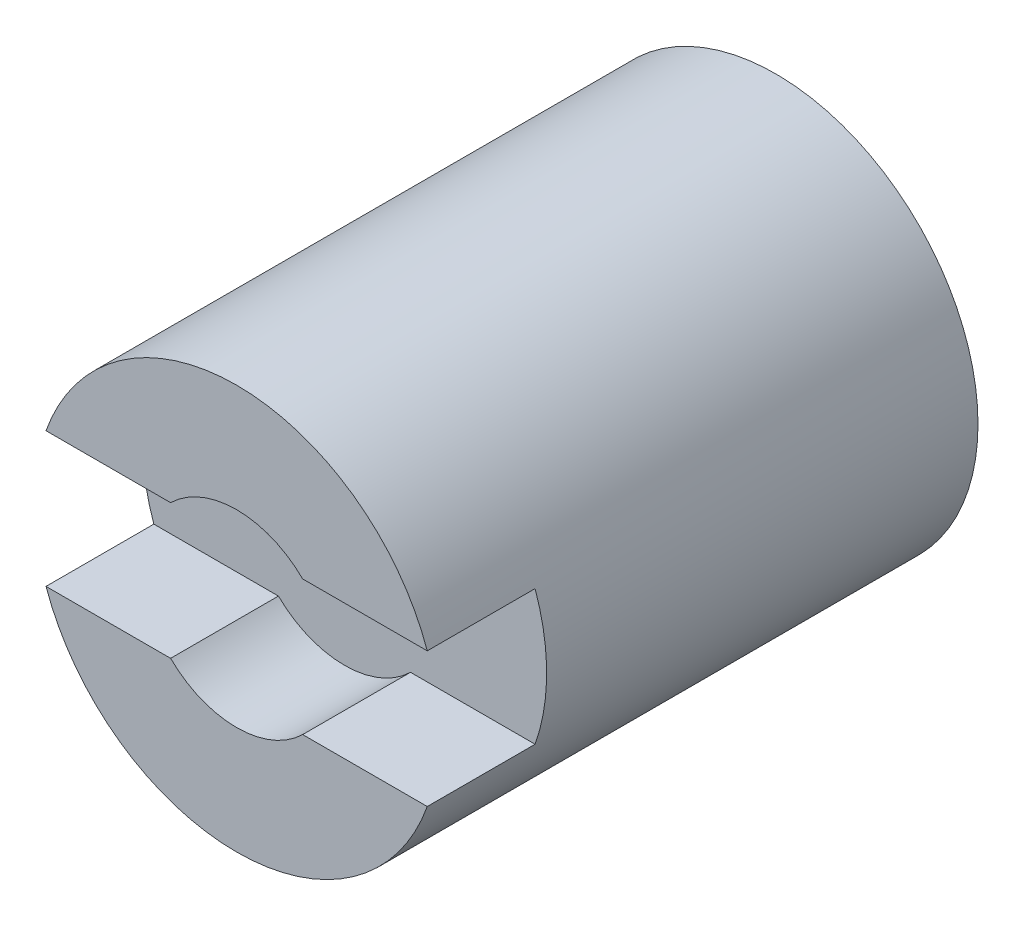
SolidWorks part; units mm, degrees
ref_plane "Спереди" through (0, 0, 0) normal (0, 0, 1) x (1, 0, 0)
ref_plane "Сверху" through (0, 0, 0) normal (0, 1, 0) x (1, 0, 0)
ref_plane "Справа" through (0, 0, 0) normal (1, 0, 0) x (0, 0, -1)
sketch "Эскиз1" plane through (0, 0, 0) normal (0, 0, 1) x (1, 0, 0)
  circle A0 centre (0, 0) radius 7.5
  dimension "D1" = 15
extrude "Бобышка-Вытянуть1" add sketch "Эскиз1" along normal blind 20
sketch "Эскиз2" plane through (0, 0, 20) normal (0, 0, 1) x (1, 0, 0)
  circle A0 centre (0, 0) radius 3.5
  dimension "D1" = 7
extrude "Вырез-Вытянуть1" cut sketch "Эскиз2" against normal blind 4
sketch "Эскиз3" plane through (0, 0, 0) normal (0, 0, -1) x (-1, 0, 0)
  circle A0 centre (0, 0) radius 1.75
  dimension "D1" = 3.5
extrude "Вырез-Вытянуть2" cut sketch "Эскиз3" against normal blind 14
sketch "Эскиз4" plane through (0, 0, 0) normal (0, 1, 0) x (1, 0, 0)
  line L0 (0, 0) -> (0, -7) construction
  circle A0 centre (0, -7) radius 1.4
  dimension "D2" = 2.8
  dimension "D1" = 7
extrude "Вырез-Вытянуть3" cut sketch "Эскиз4" against normal blind 14
sketch "Эскиз5" plane through (0, 0, 20) normal (0, 0, 1) x (1, 0, 0)
  line L0 (-9, -2.5) -> (9, 2.5) construction
  line L1 (-9, 2.5) -> (9, 2.5)
  line L2 (-9, 2.5) -> (-9, -2.5)
  line L3 (-9, -2.5) -> (9, -2.5)
  line L4 (9, 2.5) -> (9, -2.5)
  dimension "D1" = 5
  dimension "D2" = 18
extrude "Вырез-Вытянуть4" cut sketch "Эскиз5" against normal blind 4
